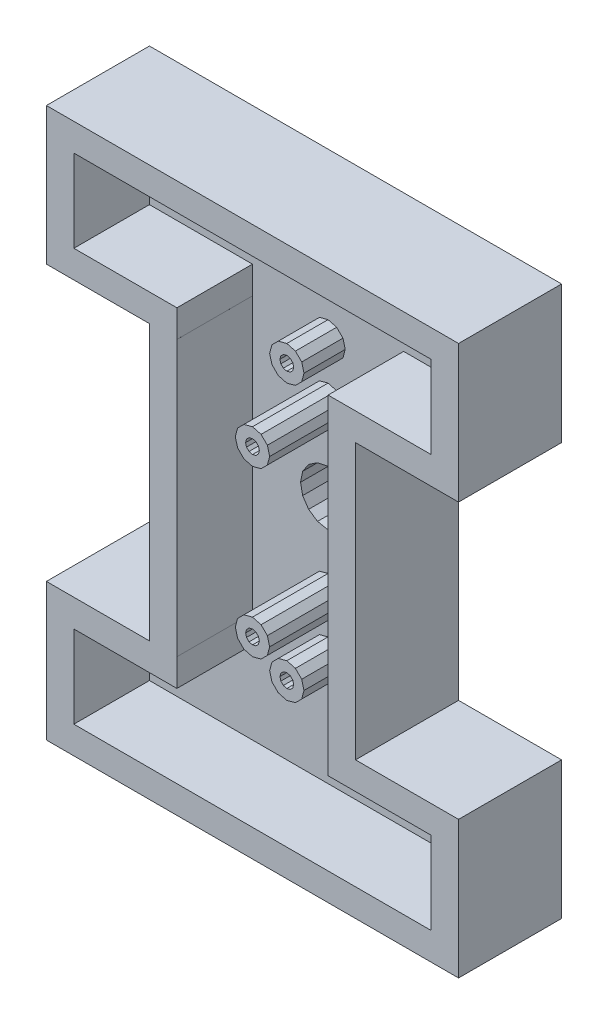
SolidWorks part; units mm, degrees
ref_plane "Front Plane" through (0, 0, 0) normal (0, 0, 1) x (1, 0, 0)
ref_plane "Top Plane" through (0, 0, 0) normal (0, 1, 0) x (1, 0, 0)
ref_plane "Right Plane" through (0, 0, 0) normal (1, 0, 0) x (0, 0, -1)
ref_plane "Plane1" through (0, 0, 15) normal (0, 0, 1) x (1, 0, 0)
sketch "Sketch1" plane through (0, 0, 15) normal (0, 0, 1) x (1, 0, 0)
  line L0 (-13.672, -17.751) -> (46.329, -17.751)
  line L1 (46.329, -17.751) -> (46.329, 62.251)
  line L2 (46.329, 62.251) -> (-13.672, 62.251)
  line L3 (-13.672, 62.251) -> (-13.672, -17.751)
extrude "Boss-Extrude1" add sketch "Sketch1" against normal blind 15.001
sketch "Sketch2" plane through (0, 0, -0.001) normal (0, 0, -1) x (-1, 0, 0)
  line L0 (-46.329, 42.249) -> (-46.329, 2.251)
  line L1 (-46.329, 2.251) -> (-31.329, 2.251)
  line L2 (-31.329, 2.251) -> (-31.329, 42.249)
  line L3 (-31.329, 42.249) -> (-46.329, 42.249)
extrude "Cut-Extrude1" cut sketch "Sketch2" against normal through all
sketch "Sketch3" plane through (0, 0, -0.001) normal (0, 0, -1) x (-1, 0, 0)
  line L0 (13.672, 42.249) -> (-1.328, 42.249)
  line L1 (-1.328, 42.249) -> (-1.328, 2.251)
  line L2 (-1.328, 2.251) -> (13.672, 2.251)
  line L3 (13.672, 2.251) -> (13.672, 42.249)
extrude "Cut-Extrude2" cut sketch "Sketch3" against normal through all
sketch "Sketch4" plane through (0, 0, 15) normal (0, 0, 1) x (1, 0, 0)
  line L0 (27.332, 42.25) -> (27.332, 46.247)
  line L1 (27.332, 46.247) -> (42.331, 46.247)
  line L2 (42.331, 46.247) -> (42.331, 58.253)
  line L3 (42.331, 58.253) -> (-9.674, 58.253)
  line L4 (-9.674, 58.253) -> (-9.674, 46.247)
  line L5 (-9.674, 46.247) -> (5.325, 46.247)
  line L6 (5.325, 46.247) -> (5.325, 42.25)
  line L7 (5.325, 42.25) -> (5.326, 42.25)
  line L8 (5.326, 42.25) -> (5.326, 2.249)
  line L9 (5.326, 2.249) -> (5.325, 2.249)
  line L10 (5.325, 2.249) -> (5.325, -1.747)
  line L11 (5.325, -1.747) -> (-9.674, -1.747)
  line L12 (-9.674, -1.747) -> (-9.674, -13.753)
  line L13 (-9.674, -13.753) -> (42.331, -13.753)
  line L14 (42.331, -13.753) -> (42.331, -1.747)
  line L15 (42.331, -1.747) -> (27.332, -1.747)
  line L16 (27.332, -1.747) -> (27.332, 2.249)
  line L17 (27.332, 2.249) -> (27.331, 2.249)
  line L18 (27.331, 2.249) -> (27.331, 42.25)
  line L19 (27.331, 42.25) -> (27.332, 42.25)
extrude "Cut-Extrude3" cut sketch "Sketch4" against normal blind 11.003
sketch "Sketch5" plane through (0, 0, 3.997) normal (0, 0, 1) x (1, 0, 0)
  line L0 (16.328, 4.751) -> (17.579, 4.415)
  line L1 (17.579, 4.415) -> (18.494, 3.5)
  line L2 (18.494, 3.5) -> (18.829, 2.25)
  line L3 (18.829, 2.25) -> (18.494, 1)
  line L4 (18.494, 1) -> (17.579, 0.085)
  line L5 (17.579, 0.085) -> (16.328, -0.25)
  line L6 (16.328, -0.25) -> (15.078, 0.085)
  line L7 (15.078, 0.085) -> (14.163, 1)
  line L8 (14.163, 1) -> (13.828, 2.25)
  line L9 (13.828, 2.25) -> (14.163, 3.5)
  line L10 (14.163, 3.5) -> (15.078, 4.415)
  line L11 (15.078, 4.415) -> (16.328, 4.751)
extrude "Boss-Extrude2" add sketch "Sketch5" along normal blind 6.004
sketch "Sketch6" plane through (0, 0, -0.001) normal (0, 0, -1) x (-1, 0, 0)
  line L0 (-16.83, 3.114) -> (-17.197, 2.748)
  line L1 (-17.197, 2.748) -> (-17.331, 2.248)
  line L2 (-17.331, 2.248) -> (-17.197, 1.747)
  line L3 (-17.197, 1.747) -> (-16.83, 1.381)
  line L4 (-16.83, 1.381) -> (-16.328, 1.247)
  line L5 (-16.328, 1.247) -> (-15.827, 1.381)
  line L6 (-15.827, 1.381) -> (-15.46, 1.747)
  line L7 (-15.46, 1.747) -> (-15.325, 2.248)
  line L8 (-15.325, 2.248) -> (-15.46, 2.748)
  line L9 (-15.46, 2.748) -> (-15.827, 3.114)
  line L10 (-15.827, 3.114) -> (-16.328, 3.248)
  line L11 (-16.328, 3.248) -> (-16.83, 3.114)
extrude "Cut-Extrude4" cut sketch "Sketch6" against normal through all
sketch "Sketch7" plane through (0, 0, -0.001) normal (0, 0, -1) x (-1, 0, 0)
  line L0 (-13.498, 19.419) -> (-12.63, 20.718)
  line L1 (-12.63, 20.718) -> (-12.325, 22.25)
  line L2 (-12.325, 22.25) -> (-12.63, 23.782)
  line L3 (-12.63, 23.782) -> (-13.498, 25.081)
  line L4 (-13.498, 25.081) -> (-14.797, 25.948)
  line L5 (-14.797, 25.948) -> (-16.328, 26.253)
  line L6 (-16.328, 26.253) -> (-17.86, 25.948)
  line L7 (-17.86, 25.948) -> (-19.159, 25.081)
  line L8 (-19.159, 25.081) -> (-20.027, 23.782)
  line L9 (-20.027, 23.782) -> (-20.331, 22.25)
  line L10 (-20.331, 22.25) -> (-20.027, 20.718)
  line L11 (-20.027, 20.718) -> (-19.159, 19.419)
  line L12 (-19.159, 19.419) -> (-17.86, 18.552)
  line L13 (-17.86, 18.552) -> (-16.328, 18.247)
  line L14 (-16.328, 18.247) -> (-14.797, 18.552)
  line L15 (-14.797, 18.552) -> (-13.498, 19.419)
extrude "Cut-Extrude5" cut sketch "Sketch7" against normal through all
sketch "Sketch8" plane through (0, 0, 3.997) normal (0, 0, 1) x (1, 0, 0)
  line L0 (15.078, 40.085) -> (14.163, 41)
  line L1 (14.163, 41) -> (13.828, 42.25)
  line L2 (13.828, 42.25) -> (14.163, 43.5)
  line L3 (14.163, 43.5) -> (15.078, 44.415)
  line L4 (15.078, 44.415) -> (16.328, 44.751)
  line L5 (16.328, 44.751) -> (17.579, 44.415)
  line L6 (17.579, 44.415) -> (18.494, 43.5)
  line L7 (18.494, 43.5) -> (18.829, 42.25)
  line L8 (18.829, 42.25) -> (18.494, 41)
  line L9 (18.494, 41) -> (17.579, 40.085)
  line L10 (17.579, 40.085) -> (16.328, 39.75)
  line L11 (16.328, 39.75) -> (15.078, 40.085)
extrude "Boss-Extrude3" add sketch "Sketch8" along normal blind 6.004
sketch "Sketch9" plane through (0, 0, -0.001) normal (0, 0, -1) x (-1, 0, 0)
  line L0 (-15.827, 41.386) -> (-15.46, 41.752)
  line L1 (-15.46, 41.752) -> (-15.325, 42.252)
  line L2 (-15.325, 42.252) -> (-15.46, 42.753)
  line L3 (-15.46, 42.753) -> (-15.827, 43.119)
  line L4 (-15.827, 43.119) -> (-16.328, 43.253)
  line L5 (-16.328, 43.253) -> (-16.83, 43.119)
  line L6 (-16.83, 43.119) -> (-17.197, 42.753)
  line L7 (-17.197, 42.753) -> (-17.331, 42.252)
  line L8 (-17.331, 42.252) -> (-17.197, 41.752)
  line L9 (-17.197, 41.752) -> (-16.83, 41.386)
  line L10 (-16.83, 41.386) -> (-16.328, 41.252)
  line L11 (-16.328, 41.252) -> (-15.827, 41.386)
extrude "Cut-Extrude6" cut sketch "Sketch9" against normal through all
sketch "Sketch10" plane through (0, 0, 3.997) normal (0, 0, 1) x (1, 0, 0)
  line L0 (14.163, 9) -> (13.828, 10.25)
  line L1 (13.828, 10.25) -> (14.163, 11.5)
  line L2 (14.163, 11.5) -> (15.078, 12.415)
  line L3 (15.078, 12.415) -> (16.328, 12.75)
  line L4 (16.328, 12.75) -> (17.579, 12.415)
  line L5 (17.579, 12.415) -> (18.494, 11.5)
  line L6 (18.494, 11.5) -> (18.829, 10.25)
  line L7 (18.829, 10.25) -> (18.494, 9)
  line L8 (18.494, 9) -> (17.579, 8.085)
  line L9 (17.579, 8.085) -> (16.328, 7.75)
  line L10 (16.328, 7.75) -> (15.078, 8.085)
  line L11 (15.078, 8.085) -> (14.163, 9)
extrude "Boss-Extrude4" add sketch "Sketch10" along normal blind 11.003
sketch "Sketch11" plane through (0, 0, 15) normal (0, 0, 1) x (1, 0, 0)
  line L0 (16.83, 9.381) -> (17.197, 9.748)
  line L1 (17.197, 9.748) -> (17.331, 10.25)
  line L2 (17.331, 10.25) -> (17.197, 10.752)
  line L3 (17.197, 10.752) -> (16.83, 11.119)
  line L4 (16.83, 11.119) -> (16.328, 11.253)
  line L5 (16.328, 11.253) -> (15.827, 11.119)
  line L6 (15.827, 11.119) -> (15.46, 10.752)
  line L7 (15.46, 10.752) -> (15.325, 10.25)
  line L8 (15.325, 10.25) -> (15.46, 9.748)
  line L9 (15.46, 9.748) -> (15.827, 9.381)
  line L10 (15.827, 9.381) -> (16.328, 9.247)
  line L11 (16.328, 9.247) -> (16.83, 9.381)
extrude "Cut-Extrude7" cut sketch "Sketch11" against normal blind 11.003
sketch "Sketch12" plane through (0, 0, 3.997) normal (0, 0, 1) x (1, 0, 0)
  line L0 (17.579, 36.415) -> (18.494, 35.5)
  line L1 (18.494, 35.5) -> (18.829, 34.25)
  line L2 (18.829, 34.25) -> (18.494, 33)
  line L3 (18.494, 33) -> (17.579, 32.085)
  line L4 (17.579, 32.085) -> (16.328, 31.75)
  line L5 (16.328, 31.75) -> (15.078, 32.085)
  line L6 (15.078, 32.085) -> (14.163, 33)
  line L7 (14.163, 33) -> (13.828, 34.25)
  line L8 (13.828, 34.25) -> (14.163, 35.5)
  line L9 (14.163, 35.5) -> (15.078, 36.415)
  line L10 (15.078, 36.415) -> (16.328, 36.751)
  line L11 (16.328, 36.751) -> (17.579, 36.415)
extrude "Boss-Extrude5" add sketch "Sketch12" along normal blind 11.003
sketch "Sketch13" plane through (0, 0, 15) normal (0, 0, 1) x (1, 0, 0)
  line L0 (15.827, 35.119) -> (15.46, 34.752)
  line L1 (15.46, 34.752) -> (15.325, 34.25)
  line L2 (15.325, 34.25) -> (15.46, 33.748)
  line L3 (15.46, 33.748) -> (15.827, 33.381)
  line L4 (15.827, 33.381) -> (16.328, 33.247)
  line L5 (16.328, 33.247) -> (16.83, 33.381)
  line L6 (16.83, 33.381) -> (17.197, 33.748)
  line L7 (17.197, 33.748) -> (17.331, 34.25)
  line L8 (17.331, 34.25) -> (17.197, 34.752)
  line L9 (17.197, 34.752) -> (16.83, 35.119)
  line L10 (16.83, 35.119) -> (16.328, 35.253)
  line L11 (16.328, 35.253) -> (15.827, 35.119)
extrude "Cut-Extrude8" cut sketch "Sketch13" against normal blind 11.003
